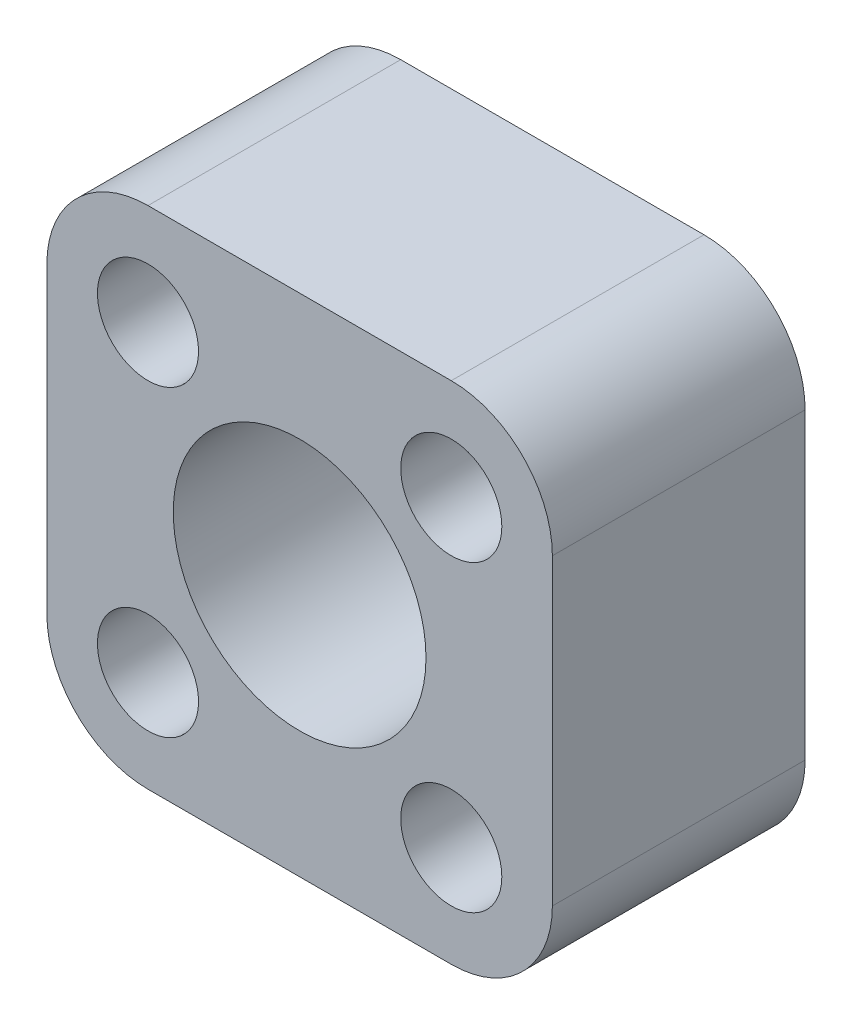
SolidWorks part; units mm, degrees
ref_plane "Plan de face" through (0, 0, 0) normal (0, 0, 1) x (1, 0, 0)
ref_plane "Plan de dessus" through (0, 0, 0) normal (0, 1, 0) x (1, 0, 0)
ref_plane "Plan de droite" through (0, 0, 0) normal (1, 0, 0) x (0, 0, -1)
sketch "Esquisse1" plane through (0, 0, 0) normal (0, 0, 1) x (1, 0, 0)
  line L1 (-3, 5) -> (3, 5)
  line L2 (-5, 3) -> (-5, -3)
  line L3 (-3, -5) -> (3, -5)
  line L4 (5, 3) -> (5, -3)
  line L5 (-5, 5) -> (5, -5) construction
  line L6 (-5, -5) -> (5, 5) construction
  arc A0 (3, 5) -> (5, 3) centre (3, 3) cw
  arc A1 (-3, 5) -> (-5, 3) centre (-3, 3) ccw
  arc A2 (3, -5) -> (5, -3) centre (3, -3) ccw
  arc A3 (-5, -3) -> (-3, -5) centre (-3, -3) ccw
  circle A4 centre (-3, 3) radius 1
  circle A5 centre (0, 0) radius 4.2426 construction
  circle A6 centre (3, 3) radius 1
  circle A7 centre (3, -3) radius 1
  circle A8 centre (-3, -3) radius 1
  circle A9 centre (0, 0) radius 2.5
  point P0 (0, 0)
  point P30 (0, 0)
  dimension "D3" = 2
  dimension "D4" = 2
  dimension "D6" = 5
  dimension "D1" = 10
  dimension "D2" = 10
  dimension "D5" = 4
extrude "Boss.-Extru.1" add sketch "Esquisse1" along normal blind 5
